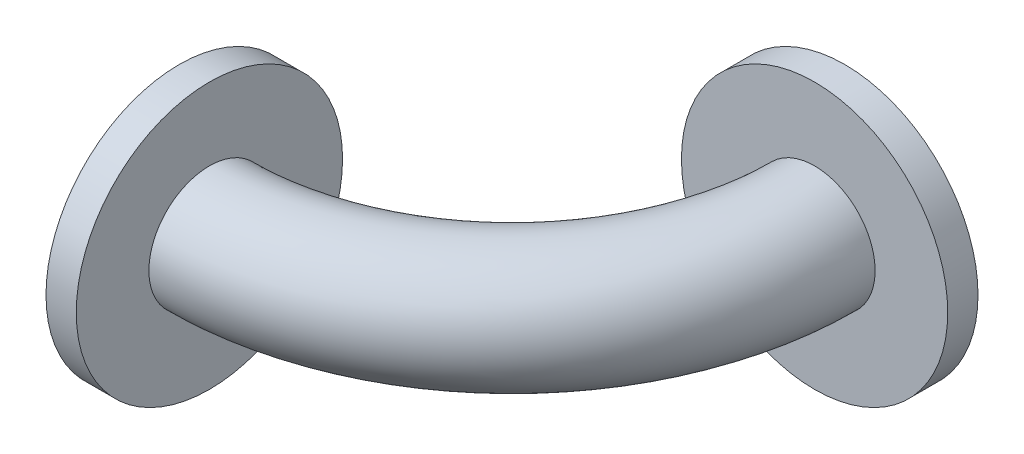
SolidWorks part; units mm, degrees
ref_plane "前视基准面" through (0, 0, 0) normal (0, 0, 1) x (1, 0, 0)
ref_plane "上视基准面" through (0, 0, 0) normal (0, 1, 0) x (1, 0, 0)
ref_plane "右视基准面" through (0, 0, 0) normal (1, 0, 0) x (0, 0, -1)
ref_plane "基准面1" through (50, 0, 0) normal (1, 0, 0) x (0, 0, -1)
sketch "草图1" plane through (0, 0, 0) normal (0, 1, 0) x (1, 0, 0)
  arc A0 (50, 0) -> (0, -50) centre (-0.0001, 0.0001) cw
sweep "扫描2" add path "草图1" circular profile diameter 20 parameters "D3"=20
ref_plane "基准面2" through (0, 50, 0) normal (0, 1, 0) x (1, 0, 0)
ref_plane "基准面3" through (0, 0, 50) normal (0, 0, 1) x (1, 0, 0)
sketch "草图11" plane through (0, 0, 0) normal (0, 0, 1) x (1, 0, 0)
  circle A0 centre (50, 0) radius 22
extrude "凸台-拉伸4" add sketch "草图11" against normal blind 5
ref_plane "基准面4" through (-5, 0, 0) normal (1, 0, 0) x (0, 0, -1)
sketch "草图16" plane through (0, 0, 0) normal (1, 0, 0) x (0, 0, -1)
  circle A0 centre (-50, 0) radius 22
extrude "凸台-拉伸7" add sketch "草图16" against normal blind 5
